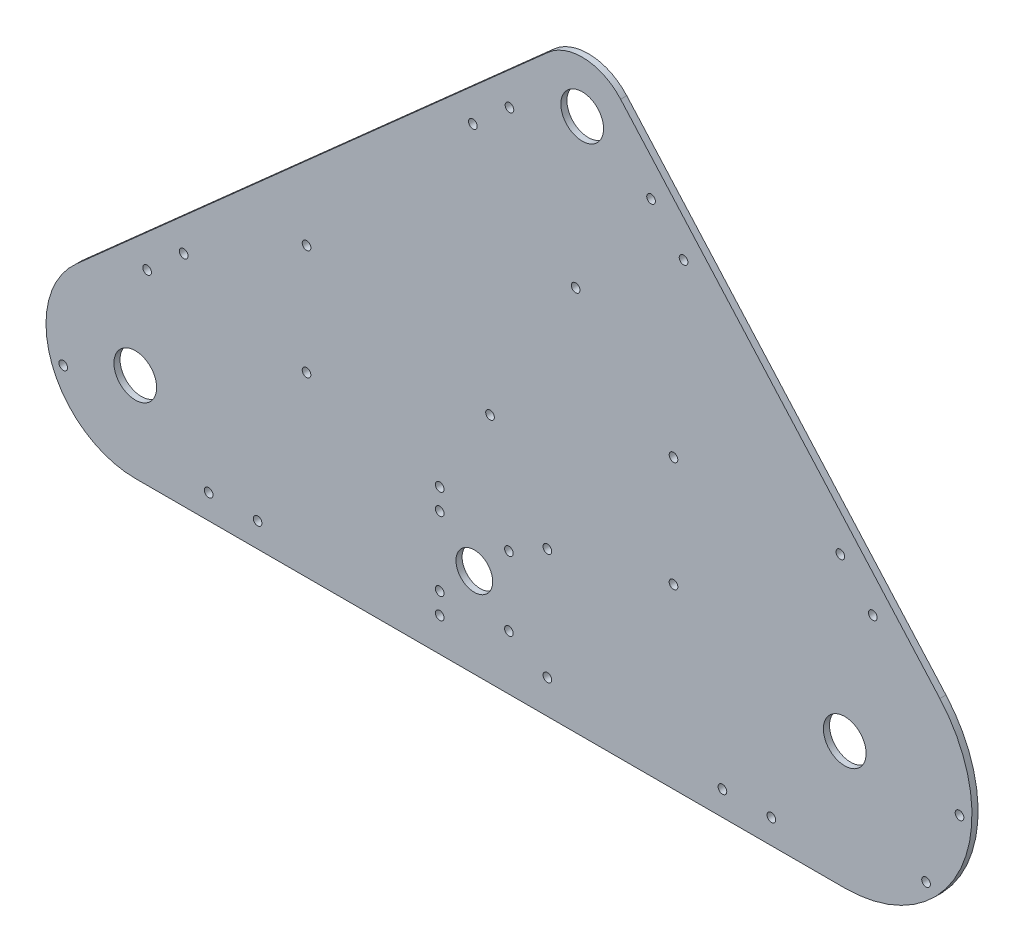
SolidWorks part; units mm, degrees
ref_plane "Front Plane" through (0, 0, 0) normal (0, 0, 1) x (1, 0, 0)
ref_plane "Top Plane" through (0, 0, 0) normal (0, 1, 0) x (1, 0, 0)
ref_plane "Right Plane" through (0, 0, 0) normal (1, 0, 0) x (0, 0, -1)
sketch "Sketch1" plane through (0, 0, 0) normal (0, 0, 1) x (1, 0, 0)
  line L4 (-188.2646, 81.0118) -> (56.8098, 298.7045)
  line L5 (-157.48, 0) -> (210.82, 0)
  line L9 (94.461, 296.4767) -> (260.194, 109.8976)
  line L10 (-157.48, 46.355) -> (18.5166, 46.355) construction
  line L11 (15.767, 41.5925) -> (21.2662, 41.5925) construction
  line L12 (21.2662, 41.5925) -> (24.0159, 46.355) construction
  line L13 (24.0159, 46.355) -> (21.2662, 51.1175) construction
  line L14 (21.2662, 51.1175) -> (15.767, 51.1175) construction
  line L15 (15.767, 51.1175) -> (13.0173, 46.355) construction
  line L16 (13.0173, 46.355) -> (15.767, 41.5925) construction
  line L19 (0.5561, 64.3155) -> (36.4771, 64.3155) construction
  line L20 (0.5561, 64.3155) -> (0.5561, 28.3945) construction
  line L21 (0.5561, 28.3945) -> (36.4771, 28.3945) construction
  line L22 (36.4771, 64.3155) -> (36.4771, 28.3945) construction
  line L23 (0.5561, 64.3155) -> (36.4771, 28.3945) construction
  line L24 (0.5561, 28.3945) -> (36.4771, 64.3155) construction
  arc A3 (-188.2646, 81.0118) -> (-157.48, 0) centre (-157.48, 46.355) ccw
  arc A4 (210.82, 0) -> (260.194, 109.8976) centre (210.82, 66.04) ccw
  arc A5 (94.461, 296.4767) -> (56.8098, 298.7045) centre (74.5215, 278.765) ccw
  circle A7 centre (-157.48, 46.355) radius 11.0998
  circle A8 centre (74.5215, 278.765) radius 11.0998
  circle A9 centre (210.82, 66.04) radius 11.0998
  circle A10 centre (18.5166, 46.355) radius 4.7625 construction
  circle A11 centre (18.5166, 46.355) radius 9.525
  dimension "D3" = 19.685
  dimension "D4" = 90
  dimension "D5" = 232.41
  dimension "D2" = 368.3
  dimension "D6" = 92.71
  dimension "D7" = 53.34
  dimension "D8" = 132.08
  dimension "D10" = 22.1996
  dimension "D11" = 9.525
  dimension "D14" = 50.8
  dimension "D12" = 19.05
  dimension "D13" = 175.9966
extrude "Boss-Extrude1" add sketch "Sketch1" along normal blind 3.175
hole_wizard "#8 Clearance Hole1" positions "Sketch4" profile "Sketch5" hole size "#8" standard "ANSI Inch"
sketch "Sketch4" plane through (0, 0, 3.175) normal (0, 0, 1) x (1, 0, 0)
  point P0 (36.4771, 64.3155)
  point P3 (36.4771, 28.3945)
  point P6 (0.5561, 28.3945)
  point P9 (0.5561, 64.3155)
sketch "Sketch5" plane through (36.4771, 64.3155, 3.175) normal (1, 0, 0) x (0, -1, 0)
  line L0 (0, 0) -> (0, 14.0507)
  line L1 (0, 14.0507) -> (2.2479, 12.7)
  line L2 (2.2479, 12.7) -> (2.2479, 0)
  line L5 (2.2479, 0) -> (0, 0)
  line L10 (0, 14.0507) -> (-2.2479, 12.7) construction
  line L11 (0, -6.35) -> (0, 107.95) construction
  dimension "Hole Dia." = 4.4958
  dimension "Hole Depth" = 12.7
  dimension "Drill Angle" = 118
sketch "Sketch6" plane through (0, 0, 3.175) normal (0, 0, 1) x (1, 0, 0)
  line L0 (56.8098, 298.7045) -> (-188.2646, 81.0118) construction
  line L1 (-157.48, 0) -> (210.82, 0) construction
  line L2 (260.194, 109.8976) -> (94.461, 296.4767) construction
  line L3 (-157.48, 46.355) -> (-188.2646, 81.0118) construction
  line L4 (-157.48, 46.355) -> (-157.48, 0) construction
  line L5 (210.82, 66.04) -> (210.82, 0) construction
  line L6 (210.82, 66.04) -> (260.194, 109.8976) construction
  line L7 (74.5215, 278.765) -> (56.8098, 298.7045) construction
  line L8 (94.461, 296.4767) -> (260.194, 109.8976) construction
  line L10 (74.5215, 278.765) -> (94.461, 296.4767) construction
  line L11 (26.67, 271.9322) -> (26.67, 0) construction
  line L12 (-188.2646, 81.0118) -> (56.8098, 298.7045) construction
  line L13 (-157.48, 0) -> (210.82, 0) construction
  line L14 (210.82, 66.04) -> (276.7447, 62.1393) construction
  line L15 (121.92, 92.075) -> (-68.58, 92.075) construction
  line L16 (121.92, 92.075) -> (121.92, 149.225) construction
  line L17 (121.92, 149.225) -> (-68.58, 149.225) construction
  line L18 (-68.58, 92.075) -> (-68.58, 149.225) construction
  line L19 (121.92, 92.075) -> (-68.58, 149.225) construction
  line L20 (121.92, 149.225) -> (-68.58, 92.075) construction
  line L21 (210.82, 66.04) -> (257.5173, 19.3427) construction
  line L22 (-157.48, 46.355) -> (-200.8119, 29.8888) construction
  line L23 (56.4361, 17.4625) -> (0.5561, 17.4625) construction
  line L24 (56.4361, 17.4625) -> (56.4361, 75.2475) construction
  line L25 (56.4361, 75.2475) -> (0.5561, 75.2475) construction
  line L26 (0.5561, 17.4625) -> (0.5561, 75.2475) construction
  arc A0 (210.82, 0) -> (260.194, 109.8976) centre (210.82, 66.04) ccw construction
  arc A1 (-188.2646, 81.0118) -> (-157.48, 0) centre (-157.48, 46.355) ccw construction
  point P0 (-119.38, 12.7)
  point P1 (-93.98, 12.7)
  point P2 (147.32, 12.7)
  point P3 (172.72, 12.7)
  point P4 (-151.3455, 96.8192)
  point P5 (-132.3555, 113.6875)
  point P6 (17.7689, 247.0388)
  point P7 (36.7589, 263.9071)
  point P8 (110.2685, 259.5575)
  point P9 (127.1368, 240.5675)
  point P12 (208.5283, 148.9385)
  point P13 (225.3966, 129.9484)
  point P44 (26.67, 120.65)
  point P50 (71.12, 200.025)
  point P60 (-194.876, 32.1444)
  point P61 (270.3947, 62.515)
  point P62 (253.0272, 23.8328)
  point P66 (18.5166, 46.355)
  point P68 (0.5561, 28.3945)
  point P69 (0.5561, 46.355)
  dimension "D28" = 6.35
  dimension "D1" = 12.7
  dimension "D2" = 12.7
  dimension "D3" = 12.7
  dimension "D4" = 12.7
  dimension "D5" = 12.7
  dimension "D6" = 25.4
  dimension "D7" = 38.1
  dimension "D8" = 38.1
  dimension "D9" = 25.4
  dimension "D10" = 25.4
  dimension "D11" = 12.7
  dimension "D12" = 12.7
  dimension "D13" = 25.4
  dimension "D14" = 38.1
  dimension "D15" = 12.7
  dimension "D16" = 12.7
  dimension "D17" = 38.1
  dimension "D18" = 25.4
  dimension "D19" = 25.4
  dimension "D20" = 38.1
  dimension "D21" = 38.1
  dimension "D22" = 184.15
  dimension "D23" = 57.15
  dimension "D24" = 190.5
  dimension "D25" = 120.65
  dimension "D26" = 45
  dimension "D27" = 45
  dimension "D29" = 6.35
  dimension "D30" = 6.35
  dimension "D31" = 50.8
  dimension "D32" = 50.8
  dimension "D33" = 57.785
  dimension "D34" = 55.88
hole_wizard "#8 Clearance Hole2" positions "Sketch7" profile "Sketch8" hole size "#8" standard "ANSI Inch" end condition through all
sketch "Sketch7" plane through (0, 0, 3.175) normal (0, 0, 1) x (1, 0, 0)
  point P0 (17.7689, 247.0388)
  point P3 (36.7589, 263.9071)
  point P6 (110.2685, 259.5575)
  point P9 (127.1368, 240.5675)
  point P12 (208.5283, 148.9385)
  point P15 (225.3966, 129.9484)
  point P18 (270.3947, 62.515)
  point P21 (253.0272, 23.8328)
  point P24 (172.72, 12.7)
  point P27 (147.32, 12.7)
  point P30 (-93.98, 12.7)
  point P33 (-119.38, 12.7)
  point P36 (-194.876, 32.1444)
  point P39 (-151.3455, 96.8192)
  point P42 (-132.3555, 113.6875)
  point P45 (-68.58, 149.225)
  point P48 (-68.58, 92.075)
  point P51 (121.92, 92.075)
  point P54 (121.92, 149.225)
  point P57 (71.12, 200.025)
  point P61 (26.67, 120.65)
  point P64 (0.5561, 75.2475)
  point P67 (56.4361, 75.2475)
  point P70 (56.4361, 17.4625)
  point P73 (0.5561, 17.4625)
sketch "Sketch8" plane through (17.7689, 247.0388, 3.175) normal (1, 0, 0) x (0, -1, 0)
  line L0 (0, 0) -> (0, 3.175)
  line L1 (0, 3.175) -> (2.2479, 3.175)
  line L2 (2.2479, 3.175) -> (2.2479, 0)
  line L5 (2.2479, 0) -> (0, 0)
  line L11 (0, -6.35) -> (0, 107.95) construction
  dimension "Thru Hole Dia." = 4.4958
  dimension "Thru Hole Depth" = 3.175
